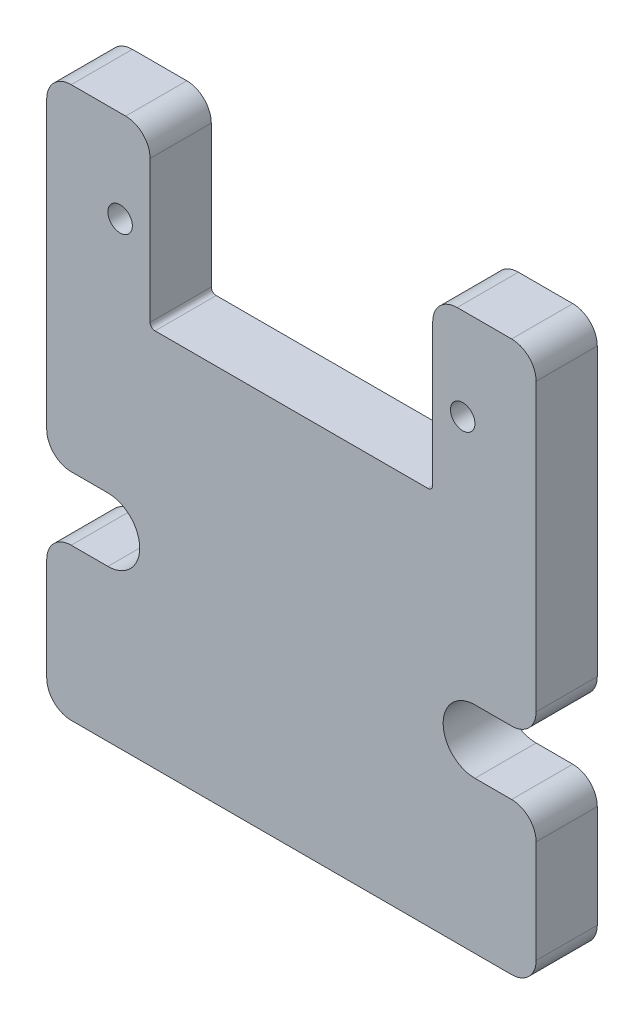
SolidWorks part; units mm, degrees
ref_plane "Plan de face" through (0, 0, 0) normal (0, 0, 1) x (1, 0, 0)
ref_plane "Plan de dessus" through (0, 0, 0) normal (0, 1, 0) x (1, 0, 0)
ref_plane "Plan de droite" through (0, 0, 0) normal (1, 0, 0) x (0, 0, -1)
sketch "Esquisse1" plane through (0, 0, 0) normal (0, 0, 1) x (1, 0, 0)
  line L0 (0, 30) -> (40, 30) construction
  line L1 (0, 0) -> (40, 0)
  line L2 (0, 0) -> (0, 60)
  line L3 (0, 60) -> (40, 60)
  line L4 (40, 0) -> (40, 60)
  line L5 (0, 0) -> (40, 60) construction
  line L6 (0, 60) -> (40, 0) construction
  circle A0 centre (5, 30) radius 2.6
  circle A1 centre (35, 30) radius 2.6
  point P4 (20, 30)
  dimension "D1" = 5.2
  dimension "D2" = 5.2
  dimension "D3" = 40
  dimension "D4" = 5
  dimension "D5" = 30
  dimension "D6" = 5
  dimension "D7" = 30
extrude "Boss.-Extru.1" add sketch "Esquisse1" along normal blind 5
sketch "Esquisse2" plane through (0, 0, 5) normal (0, 0, 1) x (1, 0, 0)
  line L0 (5, 30) -> (0, 30) construction
  line L1 (0, 60) -> (0, 0) construction
  line L2 (5, 27.4) -> (0, 27.4)
  line L3 (5, 32.6) -> (0, 32.6)
  line L4 (35, 30) -> (40, 30) construction
  line L5 (40, 0) -> (40, 60) construction
  line L6 (35, 32.6) -> (40, 32.6)
  line L7 (35, 27.4) -> (40, 27.4)
  line L8 (40, 60) -> (0, 60) construction
  line L9 (8.45, 60) -> (31.55, 60)
  line L10 (8.45, 60) -> (8.45, 46)
  line L11 (8.45, 46) -> (31.55, 46)
  line L12 (31.55, 60) -> (31.55, 46)
  line L13 (8.45, 60) -> (31.55, 46) construction
  line L14 (8.45, 46) -> (31.55, 60) construction
  line L15 (20, 0) -> (20, 53) construction
  line L16 (0, 0) -> (40, 0) construction
  line L17 (5, 30) -> (35, 30) construction
  line L18 (8.45, 14) -> (31.55, 0) construction
  line L19 (8.45, 0) -> (31.55, 14) construction
  line L20 (31.55, 0) -> (31.55, 14)
  line L21 (8.45, 14) -> (31.55, 14)
  line L22 (8.45, 0) -> (8.45, 14)
  line L23 (8.45, 0) -> (31.55, 0)
  arc A0 (5, 27.4) -> (5, 32.6) centre (5, 30) ccw
  arc A1 (0, 32.6) -> (0, 27.4) centre (0, 30) ccw
  arc A2 (35, 32.6) -> (35, 27.4) centre (35, 30) ccw
  arc A3 (40, 27.4) -> (40, 32.6) centre (40, 30) ccw
  circle A4 centre (5, 30) radius 2.6 construction
  circle A5 centre (35, 30) radius 2.6 construction
  point P5 (2.5, 30)
  point P10 (37.5, 30)
  point P28 (20, 53)
  point P41 (20, 7)
  dimension "D1" = 23.1
  dimension "D2" = 14
extrude "Enlèv. mat.-Extru.1" cut sketch "Esquisse2" against normal through all
fillet "Congé1" radius 2 12 edges at (8.45, 60, 2.5) (31.55, 60, 2.5) (40, 60, 2.5) (40, 32.6, 2.5) (40, 27.4, 2.5) (40, 0, 2.5) (0, 0, 2.5) (0, 27.4, 2.5) (0, 32.6, 2.5) (0, 60, 2.5) (8.45, 0, 2.5) (31.55, 0, 2.5)
fillet "Congé2" radius 0.4 4 edges at (31.55, 46, 2.5) (8.45, 46, 2.5) (8.45, 14, 2.5) (31.55, 14, 2.5)
sketch "Esquisse3" plane through (0, 0, 5) normal (0, 0, 1) x (1, 0, 0)
  line L0 (31.55, 52.5) -> (8.45, 52.5) construction
  line L1 (31.55, 46.4) -> (31.55, 58) construction
  line L2 (8.45, 58) -> (8.45, 46.4) construction
  line L3 (8.85, 46) -> (31.15, 46) construction
  line L4 (20, 52.5) -> (20, 46) construction
  line L5 (7.6, 30) -> (32.4, 30) construction
  line L6 (20, 7.5) -> (20, 14) construction
  line L7 (31.55, 7.5) -> (8.45, 7.5) construction
  circle A0 centre (34, 52.5) radius 1
  circle A1 centre (6, 52.5) radius 1
  arc A2 (5, 27.4) -> (5, 32.6) centre (5, 30) ccw construction
  arc A3 (35, 32.6) -> (35, 27.4) centre (35, 30) ccw construction
  circle A4 centre (6, 7.5) radius 1
  circle A5 centre (34, 7.5) radius 1
  dimension "D3" = 2
  dimension "D1" = 6.5
  dimension "D2" = 28
extrude "Enlèv. mat.-Extru.2" cut sketch "Esquisse3" against normal through all
sketch "Esquisse4" plane through (0, 0, 5) normal (0, 0, 1) x (1, 0, 0)
  line L0 (40, 15) -> (0, 15) construction
  line L1 (40, 2) -> (40, 25.4) construction
  line L2 (0, 25.4) -> (0, 2) construction
  line L4 (40, 15) -> (-8.0281, 15)
  line L5 (40, 15) -> (40, -24.5719)
  line L6 (40, -24.5719) -> (-8.0281, -24.5719)
  line L7 (-8.0281, 15) -> (-8.0281, -24.5719)
  line L8 (40, 15) -> (-8.0281, -24.5719) construction
  line L9 (40, -24.5719) -> (-8.0281, 15) construction
  arc A0 (35, 32.6) -> (35, 27.4) centre (35, 30) ccw construction
  point P9 (32.4, 30)
  point P13 (15.9859, -4.786)
  dimension "D1" = 15
extrude "Enlèv. mat.-Extru.3" cut sketch "Esquisse4" against normal blind 10
fillet "Congé3" radius 2 2 edges at (0, 15, 2.5) (40, 15, 2.5)
